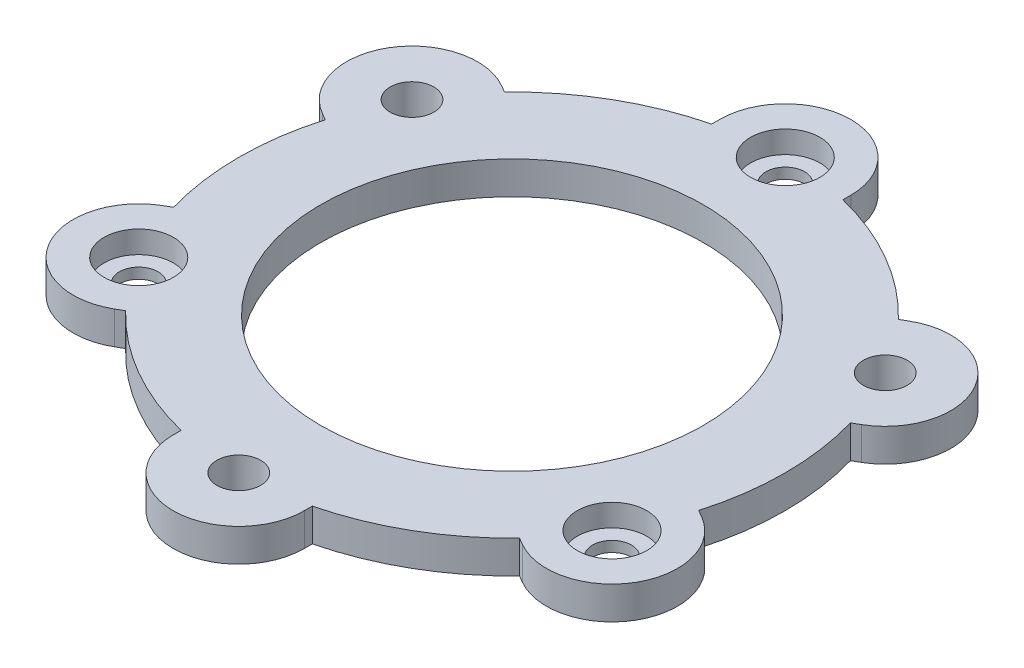
SolidWorks part; units mm, degrees
material "Delrin 2700 NC010, Low Viscosity Acetal Copolymer (SS)"
ref_plane "Front" through (0, 0, 0) normal (0, 0, 1) x (1, 0, 0)
ref_plane "Top" through (0, 0, 0) normal (0, 1, 0) x (1, 0, 0)
ref_plane "Right" through (0, 0, 0) normal (1, 0, 0) x (0, 0, -1)
sketch "Sketch1" plane through (0, 0, 0) normal (0, 1, 0) x (1, 0, 0)
  line L0 (0, 0) -> (-10.8253, -6.25) construction
  line L5 (0, 0) -> (0, -12.5) construction
  line L8 (3, 0) -> (3, -12.5)
  line L9 (-3, 0) -> (-3, -12.5)
  line L10 (1.5, -2.5981) -> (-9.3253, -8.8481)
  line L11 (-1.5, 2.5981) -> (-12.3253, -3.6519)
  line L12 (0, 0) -> (-10.8253, 6.25) construction
  line L13 (-1.5, -2.5981) -> (-12.3253, 3.6519)
  line L14 (1.5, 2.5981) -> (-9.3253, 8.8481)
  line L15 (0, 0) -> (0, 12.5) construction
  line L16 (-3, 0) -> (-3, 12.5)
  line L17 (3, 0) -> (3, 12.5)
  line L18 (0, 0) -> (10.8253, 6.25) construction
  line L19 (-1.5, 2.5981) -> (9.3253, 8.8481)
  line L20 (1.5, -2.5981) -> (12.3253, 3.6519)
  line L21 (0, 0) -> (10.8253, -6.25) construction
  line L22 (1.5, 2.5981) -> (12.3253, -3.6519)
  line L23 (-1.5, -2.5981) -> (9.3253, -8.8481)
  circle A1 centre (0, 0) radius 7.5
  arc A11 (3, 0) -> (-3, 0) centre (0, 0) ccw
  arc A12 (-3, -12.5) -> (3, -12.5) centre (0, -12.5) ccw
  circle A13 centre (0, -12.5) radius 1
  arc A15 (1.5, -2.5981) -> (-1.5, 2.5981) centre (0, 0) ccw
  arc A16 (-12.3253, -3.6519) -> (-9.3253, -8.8481) centre (-10.8253, -6.25) ccw
  circle A17 centre (-10.8253, 6.25) radius 1
  arc A18 (-1.5, -2.5981) -> (1.5, 2.5981) centre (0, 0) ccw
  arc A19 (-9.3253, 8.8481) -> (-12.3253, 3.6519) centre (-10.8253, 6.25) ccw
  circle A20 centre (0, 0) radius 8.75
  circle A21 centre (0, 0) radius 12.5
  arc A23 (-3, 0) -> (3, 0) centre (0, 0) ccw
  arc A24 (3, 12.5) -> (-3, 12.5) centre (0, 12.5) ccw
  circle A25 centre (10.8253, 6.25) radius 1
  arc A26 (-1.5, 2.5981) -> (1.5, -2.5981) centre (0, 0) ccw
  arc A27 (12.3253, 3.6519) -> (9.3253, 8.8481) centre (10.8253, 6.25) ccw
  arc A29 (1.5, 2.5981) -> (-1.5, -2.5981) centre (0, 0) ccw
  arc A30 (9.3253, -8.8481) -> (12.3253, -3.6519) centre (10.8253, -6.25) ccw
  circle A31 centre (-10.8253, -6.25) radius 1 [skipped]
  circle A32 centre (10.8253, -6.25) radius 1 [skipped]
  circle A33 centre (0, 12.5) radius 1 [skipped]
  point P6 (-5.4127, -3.125)
  point P10 (0, -6.25)
  point P22 (-5.4127, 3.125)
  point P30 (0, -15.5)
  point P32 (0, 6.25)
  point P40 (5.4127, 3.125)
  point P48 (5.4127, -3.125)
  dimension "D2" = 15
  dimension "D3" = 6
  dimension "D5" = 25
  dimension "D6" = 3
  dimension "D7" = 2
  dimension "D4" = 17.5
  dimension "D8" = 12.5
extrude "Boss-Extrude1" add sketch "Sketch1" along normal blind 1.5
sketch "Sketch2" plane through (0, 1.5, 0) normal (0, 1, 0) x (1, 0, 0)
  line L0 (0, 0) -> (0, 12.5) construction
  line L1 (0, 0) -> (10.8253, -6.25) construction
  line L2 (0, 0) -> (-10.8253, -6.25) construction
  dimension "D1" = 12.5
  dimension "D2" = 3
hole_wizard "CBORE for #0 Socket Head Cap Screw2" positions "3DSketch1" profile "Sketch5" counterbore size "#0" standard "ANSI Inch"
sketch3d "3DSketch1"
  point P0 (-10.8253, 1.5, 6.25)
  point P3 (0, 1.5, -12.5)
  point P6 (10.8253, 1.5, 6.25)
sketch "Sketch5" plane through (-10.8253, 1.5, 6.25) normal (1, 0, 0) x (0, 0, 1)
  line L0 (0, 0) -> (0, 8.0342)
  line L1 (0, 8.0342) -> (0.889, 7.5)
  line L2 (0.889, 7.5) -> (0.889, 1.016)
  line L3 (0.889, 1.016) -> (1.5875, 1.016)
  line L4 (1.5875, 1.016) -> (1.5875, 0)
  line L5 (1.5875, 0) -> (0, 0)
  line L10 (0, 8.0342) -> (-0.889, 7.5) construction
  line L11 (0, -6.35) -> (0, 107.95) construction
  dimension "Hole Dia." = 1.778
  dimension "Hole Depth" = 7.5
  dimension "C'Bore Dia." = 3.175
  dimension "C'Bore Depth" = 1.016
  dimension "Drill Angle" = 118
